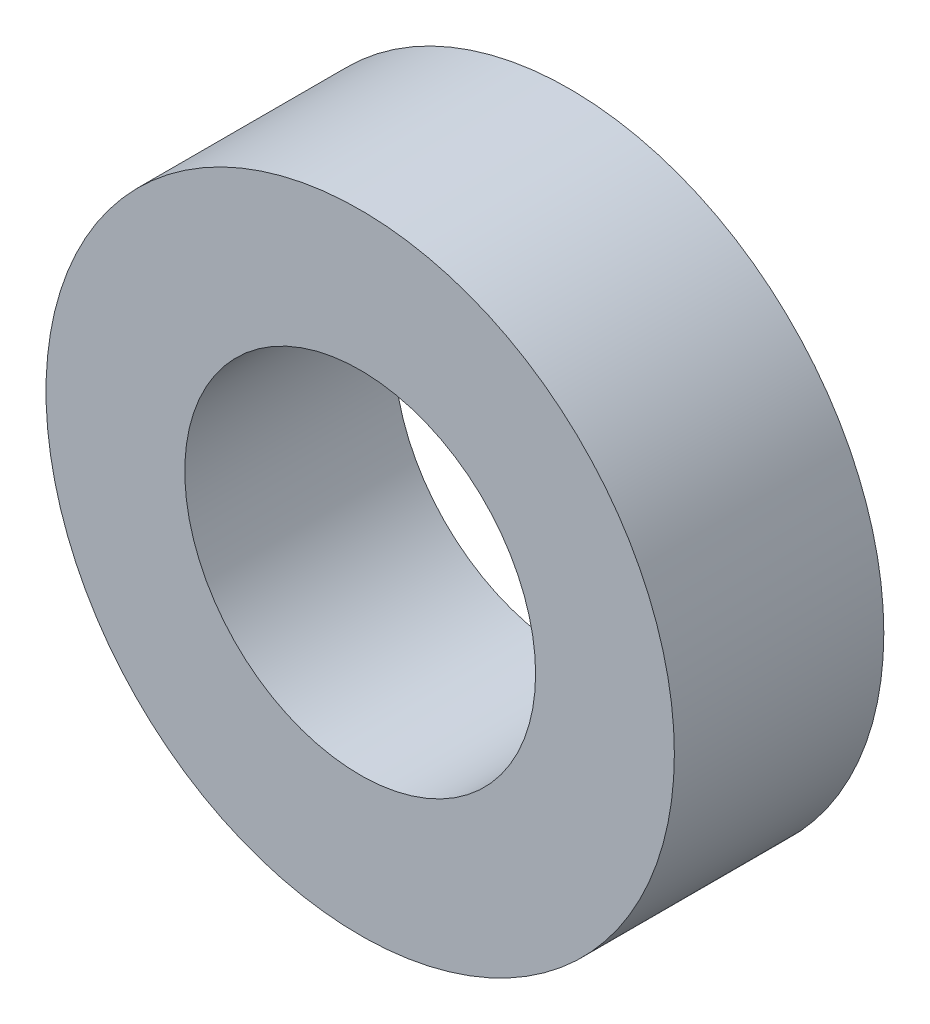
SolidWorks part; units mm, degrees
ref_plane "前视基准面" through (0, 0, 0) normal (0, 0, 1) x (1, 0, 0)
ref_plane "上视基准面" through (0, 0, 0) normal (0, 1, 0) x (1, 0, 0)
ref_plane "右视基准面" through (0, 0, 0) normal (1, 0, 0) x (0, 0, -1)
other "Configuration Table"
sketch "草图1" plane through (0, 0, 0) normal (0, 0, 1) x (1, 0, 0)
  circle A0 centre (0, 0) radius 1.675
  circle A1 centre (0, 0) radius 3
  dimension "D1" = 3.35
  dimension "D2" = 6
extrude "凸台-拉伸1" add sketch "草图1" along normal blind 2
